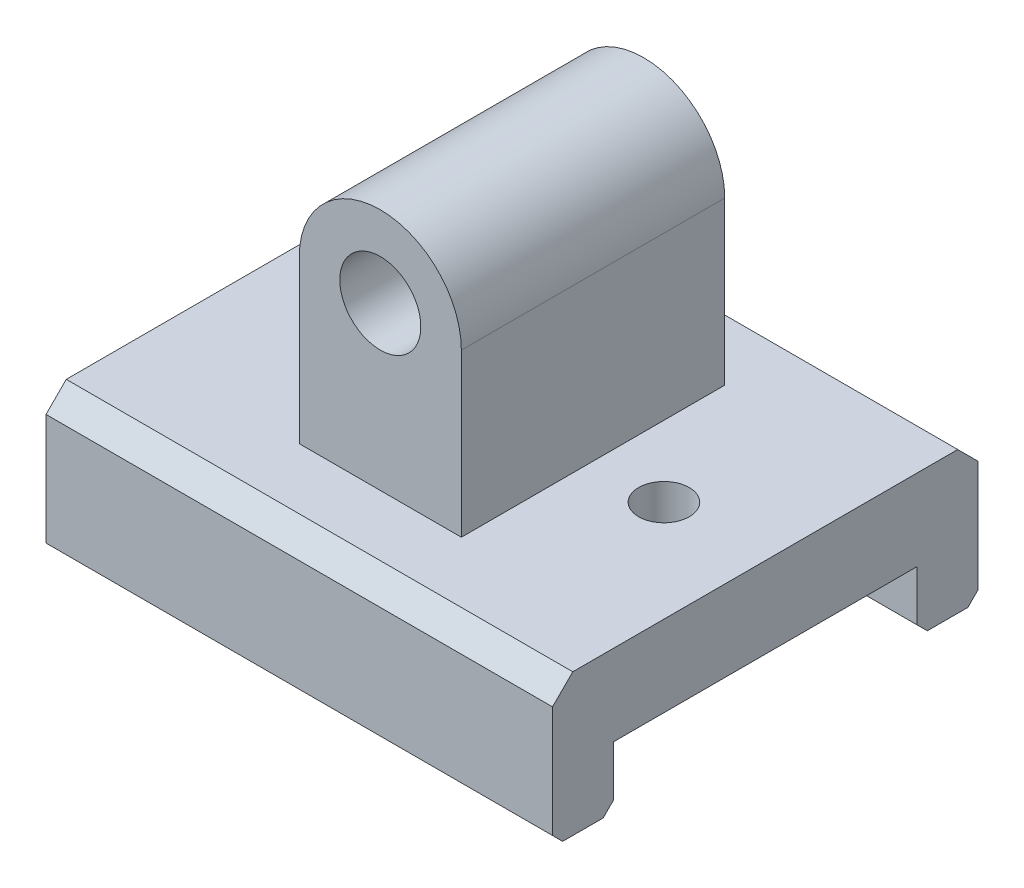
SolidWorks part; units mm, degrees
material "6063-T1"
ref_plane "前视基准面" through (0, 0, 0) normal (0, 0, 1) x (1, 0, 0)
ref_plane "上视基准面" through (0, 0, 0) normal (0, 1, 0) x (1, 0, 0)
ref_plane "右视基准面" through (0, 0, 0) normal (1, 0, 0) x (0, 0, -1)
sketch "草图1" plane through (0, 0, 0) normal (1, 0, 0) x (0, 0, -1)
  line L0 (-7.5, 0) -> (7.5, 0)
  line L1 (7.5, 0) -> (7.5, -3)
  line L2 (7.5, -3) -> (10.5, -3)
  line L3 (10.5, -3) -> (10.5, 4)
  line L4 (10.5, 4) -> (-10.5, 4)
  line L5 (-10.5, 4) -> (-10.5, -3)
  line L6 (-10.5, -3) -> (-7.5, -3)
  line L7 (-7.5, -3) -> (-7.5, 0)
  line L8 (0, 0) -> (0, 4) construction
  point P13 (0, 4)
  dimension "D1" = 15
  dimension "D2" = 3
  dimension "D3" = 3
  dimension "D4" = 4
extrude "凸台-拉伸1" add sketch "草图1" along normal blind 25
sketch "草图2" plane through (0, 0, 0) normal (0, 0, 1) x (1, 0, 0)
  line L0 (25, 4) -> (0, 4) construction
  line L1 (8.5, 12) -> (8.5, 4)
  line L2 (16.5, 12) -> (16.5, 4)
  line L3 (8.5, 4) -> (16.5, 4)
  circle A0 centre (12.5, 12) radius 2
  arc A1 (16.5, 12) -> (8.5, 12) centre (12.5, 12) ccw
  point P4 (12.5, 4)
  dimension "D1" = 8
  dimension "D2" = 4
  dimension "D3" = 4
extrude "凸台-拉伸2" add sketch "草图2" along normal mid plane 13
hole_wizard "M3 螺纹孔1" positions "草图3" profile "草图5" tap size "M3" standard "GB" end condition through all
sketch "草图3" plane through (0, 4, 0) normal (0, 1, 0) x (1, 0, 0)
  line L0 (5, 0) -> (20, 0)
  line L3 (25, 10.5) -> (0, 10.5) construction
  line L5 (0, 10.5) -> (0, -10.5) construction
  point P0 (5, 0)
  point P2 (20, 0)
  point P15 (12.5, 0)
  point P18 (12.5, 10.5)
  dimension "D1" = 5
sketch "草图5" plane through (5, 4, 0) normal (1, 0, 0) x (0, 0, 1)
  line L0 (0, 0) -> (0, 7)
  line L1 (0, 7) -> (1.25, 7)
  line L2 (1.25, 7) -> (1.25, 0)
  line L5 (1.25, 0) -> (0, 0)
  line L11 (0, -6.35) -> (0, 107.95) construction
  dimension "通孔螺纹孔钻头直径" = 2.5
  dimension "通孔螺纹孔钻头深度" = 7
cosmetic thread "孔螺蚊线1" parameters "D2"=3
cosmetic thread "孔螺蚊线2" parameters "D2"=3
chamfer "倒角1" distance 1 angle 45 2 edges at (12.5, 4, -10.5) (12.5, 4, 10.5)
chamfer "倒角2" distance 0.5 angle 45 4 edges at (12.5, -3, -7.5) (12.5, -3, 7.5) (12.5, -3, -10.5) (12.5, -3, 10.5)
